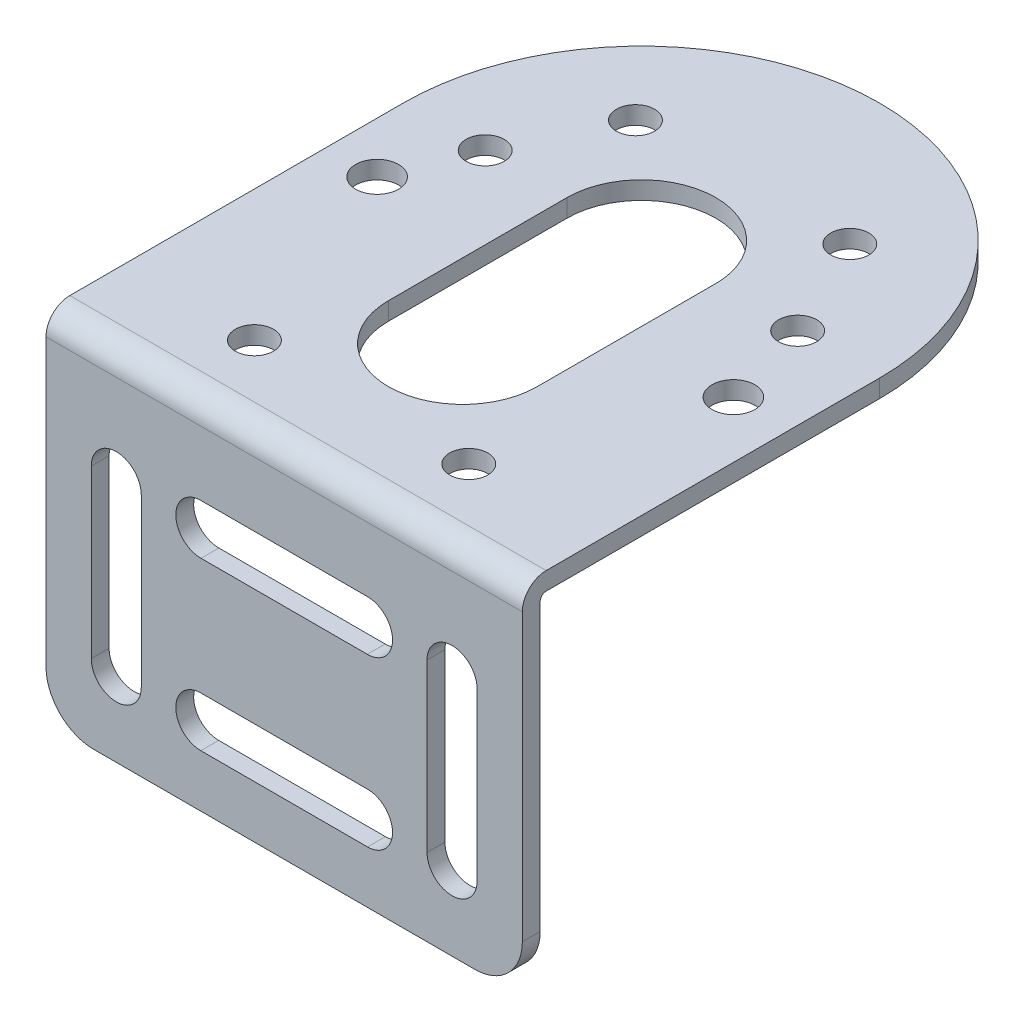
SolidWorks part; units mm, degrees
ref_plane "Front Plane" through (0, 0, 0) normal (0, 0, 1) x (1, 0, 0)
ref_plane "Top Plane" through (0, 0, 0) normal (0, 1, 0) x (1, 0, 0)
ref_plane "Right Plane" through (0, 0, 0) normal (1, 0, 0) x (0, 0, -1)
ref_plane "Plane1" through (0, -30, 0) normal (0, -1, 0) x (1, 0, 0)
sketch "Sketch1" plane through (0, -30, 0) normal (0, -1, 0) x (1, 0, 0)
  line L0 (20, 0) -> (-20, 0)
  line L1 (-20, 0) -> (-20, -30)
  line L2 (20, -30) -> (20, 0)
  arc A0 (-20, -30) -> (20, -30) centre (0, -30) ccw
extrude "Boss-Extrude1" add sketch "Sketch1" against normal blind 30
sketch "Sketch2" plane through (20, 0, 0) normal (1, 0, 0) x (0, 0, -1)
  line L0 (30, -1.5) -> (1.5, -1.5)
  line L1 (1.5, -1.5) -> (1.5, -30)
  line L2 (1.5, -30) -> (30, -30)
  line L3 (30, -30) -> (30, -1.5)
extrude "Cut-Extrude1" cut sketch "Sketch2" against normal through all
sketch "Sketch3" plane through (0, 0, 0) normal (0, 0, 1) x (1, 0, 0)
  line L0 (16.2, -23.5) -> (16.2, -9.5)
  line L1 (12, -9.5) -> (12, -23.5)
  arc A0 (16.2, -9.5) -> (12, -9.5) centre (14.1, -9.5) ccw
  arc A1 (12, -23.5) -> (16.2, -23.5) centre (14.1, -23.5) ccw
extrude "Cut-Extrude2" cut sketch "Sketch3" against normal up to next
sketch "Sketch4" plane through (0, 0, 0) normal (0, 0, 1) x (1, 0, 0)
  line L0 (-16.2, -9.5) -> (-16.2, -23.5)
  line L1 (-12, -23.5) -> (-12, -9.5)
  arc A0 (-12, -9.5) -> (-16.2, -9.5) centre (-14.1, -9.5) ccw
  arc A1 (-16.2, -23.5) -> (-12, -23.5) centre (-14.1, -23.5) ccw
extrude "Cut-Extrude3" cut sketch "Sketch4" against normal up to next
sketch "Sketch5" plane through (0, 0, 0) normal (0, 0, 1) x (1, 0, 0)
  line L0 (-6.9816, -11.5999) -> (6.9816, -11.5999)
  line L1 (7, -7.4) -> (-7, -7.4)
  arc A0 (-7, -7.4) -> (-6.9816, -11.5999) centre (-7, -9.5) ccw
  arc A1 (6.9816, -11.5999) -> (7, -7.4) centre (7, -9.5) ccw
extrude "Cut-Extrude4" cut sketch "Sketch5" against normal up to next
sketch "Sketch6" plane through (0, -1.5, 0) normal (0, -1, 0) x (1, 0, 0)
  line L0 (6.25, -30) -> (6.25, -15)
  line L1 (-6.25, -15) -> (-6.25, -30)
  arc A0 (6.25, -15) -> (-6.25, -15) centre (0, -15) ccw
  arc A1 (-6.25, -30) -> (6.25, -30) centre (0, -30) ccw
extrude "Cut-Extrude5" cut sketch "Sketch6" against normal through all
sketch "Sketch7" plane through (0, 0, -1.5) normal (0, 0, -1) x (-1, 0, 0)
  line L0 (-7, -25.6) -> (7, -25.6)
  line L1 (7, -21.4) -> (-7, -21.4)
  arc A0 (7, -25.6) -> (7, -21.4) centre (7, -23.5) ccw
  arc A1 (-7, -21.4) -> (-7, -25.6) centre (-7, -23.5) ccw
extrude "Cut-Extrude6" cut sketch "Sketch7" against normal through all
hole_wizard "M3 Clearance Hole1" positions "Sketch9" profile "Sketch8" hole size "M3" standard "ANSI Metric"
sketch "Sketch9" plane through (0, -1.5, 0) normal (0, -1, 0) x (-1, 0, 0)
  point P0 (9, 6.5)
  point P1 (-9, 6.5)
  point P2 (9, 38.5)
  point P3 (-9, 38.5)
  point P4 (13.12, 30)
  point P5 (-13.12, 30)
sketch "Sketch8" plane through (-9, -1.5, -6.5) normal (1, 0, 0) x (0, 0, -1)
  line L0 (0, 0) -> (0, 1.5)
  line L1 (0, 1.5) -> (1.6017, 1.5)
  line L2 (1.6017, 1.5) -> (1.6017, 0)
  line L5 (1.6017, 0) -> (0, 0)
  line L11 (0, -6.35) -> (0, 107.95) construction
  dimension "Thru Hole Dia." = 3.2034
  dimension "Thru Hole Depth" = 1.5
fillet "Fillet1" radius 0.5 1 edges at (0, -1.5, -1.5)
fillet "Fillet2" radius 2 1 edges at (0, 0, 0)
fillet "Fillet3" radius 4 2 edges at (20, -30, -0.75) (-20, -30, -0.75)
sketch "Sketch10" plane through (0, -30, 0) normal (0, -1, 0) x (1, 0, 0)
  line L0 (-20, -30) -> (20, -30) construction
  line L1 (-20, -30) -> (20, -30)
  arc A0 (-20, -30) -> (20, -30) centre (0, -30) ccw
extrude "Cut-Extrude7" cut sketch "Sketch10" against normal blind 28.5
sketch "Sketch11" plane through (0, 0, 0) normal (0, 1, 0) x (1, 0, 0)
  circle A0 centre (-15.7306, 23.5349) radius 1.8018
  circle A1 centre (15.2512, 22.4733) radius 1.8018
extrude "Cut-Extrude8" cut sketch "Sketch11" against normal through all
